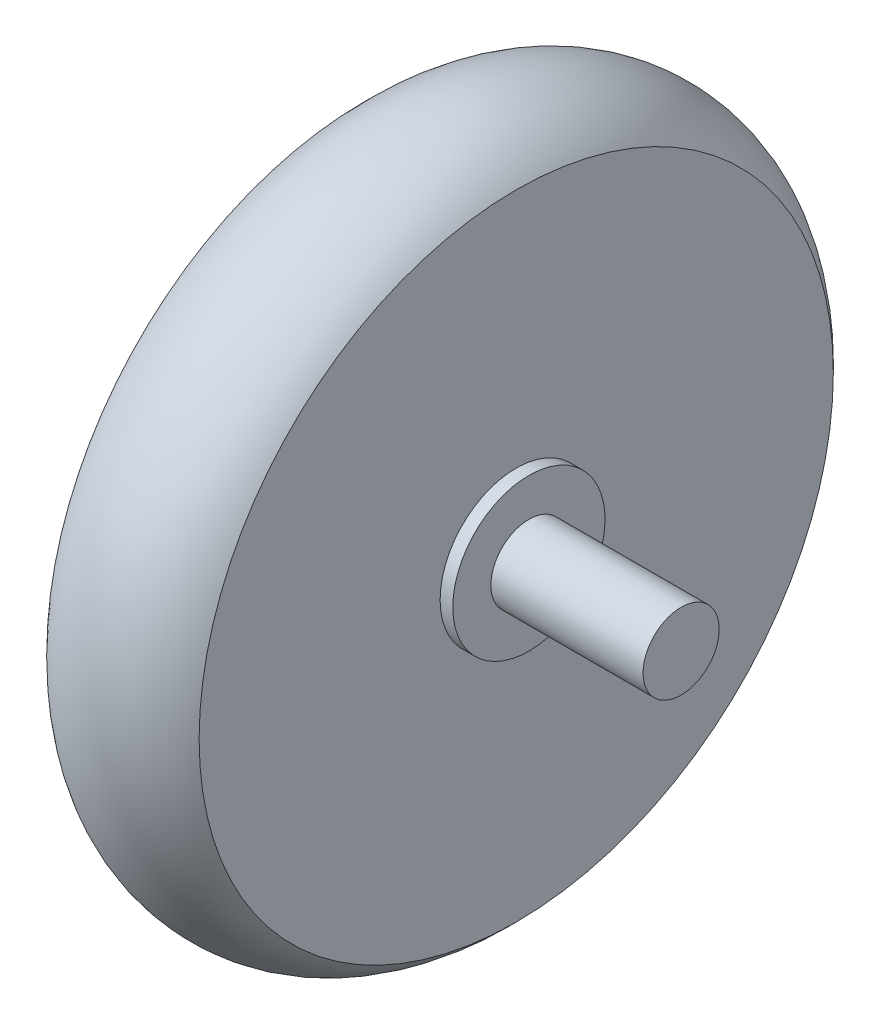
SolidWorks part; units mm, degrees
ref_plane "前视基准面" through (0, 0, 0) normal (0, 0, 1) x (1, 0, 0)
ref_plane "上视基准面" through (0, 0, 0) normal (0, 1, 0) x (1, 0, 0)
ref_plane "右视基准面" through (0, 0, 0) normal (1, 0, 0) x (0, 0, -1)
sketch "草图1" plane through (0, 0, 0) normal (0, 1, 0) x (1, 0, 0)
  line L0 (0, 0) -> (69.6045, 0) construction
  line L1 (0, -25) -> (0, 25)
  line L2 (0, 25) -> (12, 25) construction
  line L3 (0, -25) -> (12, -25) construction
  line L4 (12, 25) -> (12, 6)
  line L5 (12, -25) -> (12, -6) construction
  line L6 (12, 6) -> (13, 6)
  line L7 (12, -6) -> (13, -6) construction
  line L8 (13, 6) -> (13, 3)
  line L9 (13, -6) -> (13, -3) construction
  line L10 (13, 3) -> (25, 3)
  line L11 (13, -3) -> (25, -3) construction
  line L12 (25, 3) -> (25, -3)
  line L13 (0, 0) -> (25, 0)
  line L14 (0, 10) -> (2, 10)
  line L15 (2, 10) -> (2, 0)
  arc A0 (12, 25) -> (0, 25) centre (6, 19.7085) ccw
  point P15 (25, 0)
  point P20 (0, 0)
  point P22 (0, 0)
  dimension "D7" = 16
  dimension "D1" = 12
  dimension "D2" = 12
  dimension "D3" = 6
  dimension "D4" = 50
  dimension "D5" = 1
  dimension "D6" = 12
  dimension "D8" = 2
  dimension "D9" = 10
revolve "旋转1" add sketch "草图1" angle 360 about L0
